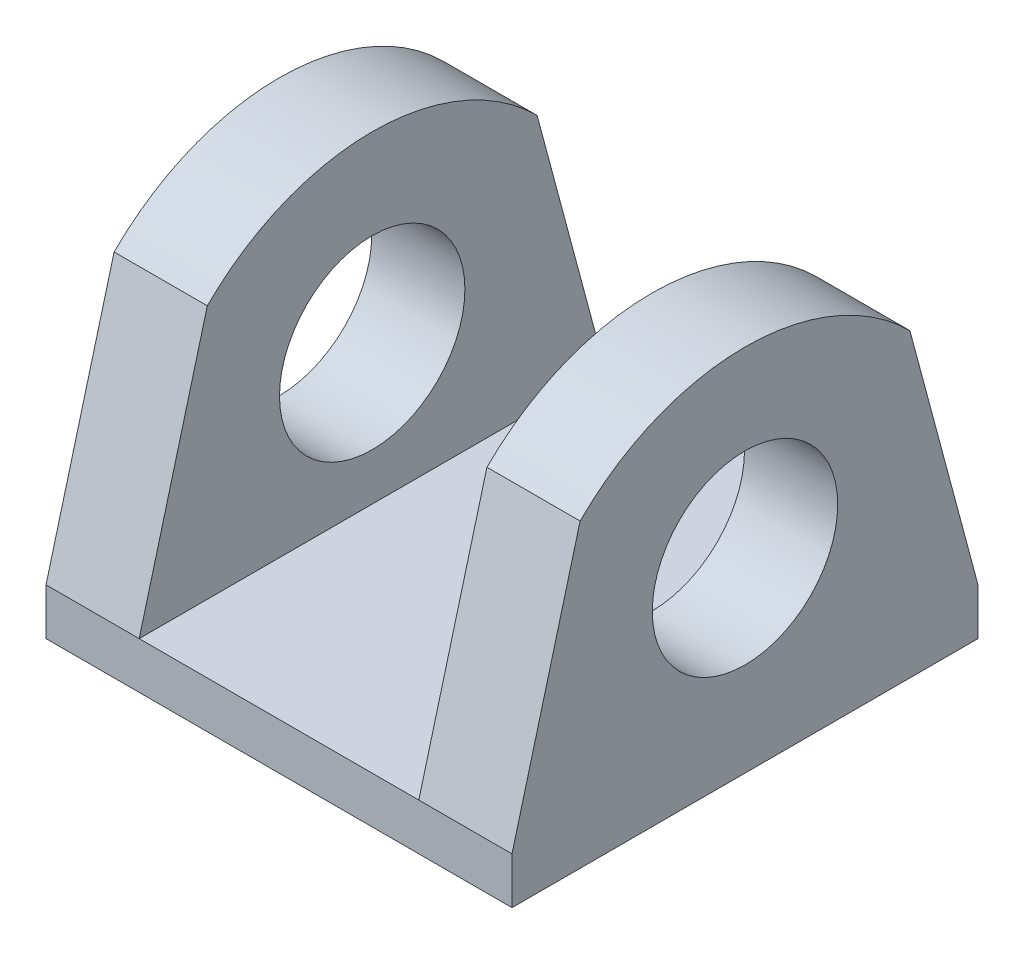
SolidWorks part; units mm, degrees
material "ABS"
ref_plane "Front Plane" through (0, 0, 0) normal (0, 0, 1) x (1, 0, 0)
ref_plane "Top Plane" through (0, 0, 0) normal (0, 1, 0) x (1, 0, 0)
ref_plane "Right Plane" through (0, 0, 0) normal (1, 0, 0) x (0, 0, -1)
sketch "Sketch1" plane through (0, 0, 0) normal (0, 1, 0) x (1, 0, 0)
  line L1 (-12.7, -12.7) -> (12.7, -12.7)
  line L2 (-12.7, -12.7) -> (-12.7, 12.7)
  line L3 (-12.7, 12.7) -> (12.7, 12.7)
  line L4 (12.7, -12.7) -> (12.7, 12.7)
  line L5 (-12.7, -12.7) -> (12.7, 12.7) construction
  line L6 (-12.7, 12.7) -> (12.7, -12.7) construction
  point P0 (0, 0)
  dimension "D1" = 25.4
  dimension "D2" = 25.4
extrude "Boss-Extrude1" add sketch "Sketch1" along normal blind 2.54
sketch "Sketch2" plane through (12.7, 0, 0) normal (1, 0, 0) x (0, 0, -1)
  line L0 (-12.7, 2.54) -> (-8.9876, 16.3948)
  line L1 (12.7, 2.54) -> (8.9876, 16.3948)
  line L2 (-12.7, 2.54) -> (12.7, 2.54) construction
  line L3 (-12.7, 2.54) -> (12.7, 2.54)
  arc A2 (-8.9876, 16.3948) -> (8.9876, 16.3948) centre (0, 7.4071) cw
  dimension "D1" = 75
  dimension "D2" = 75
extrude "Boss-Extrude2" add sketch "Sketch2" against normal blind 5.08
ref_plane "Plane1" through (0, 0, 0) normal (1, 0, 0) x (0, 0, -1)
mirror "Mirror1" about plane through (0, 0, 0) normal (1, 0, 0) of "Boss-Extrude2"
sketch "Sketch3" plane through (12.7, 0, 0) normal (1, 0, 0) x (0, 0, -1)
  line L0 (-12.7, 0) -> (12.7, 0) construction
  circle A0 centre (0, 10.16) radius 5.0532
  dimension "D1" = 10.16
extrude "Cut-Extrude1" cut sketch "Sketch3" against normal through all
